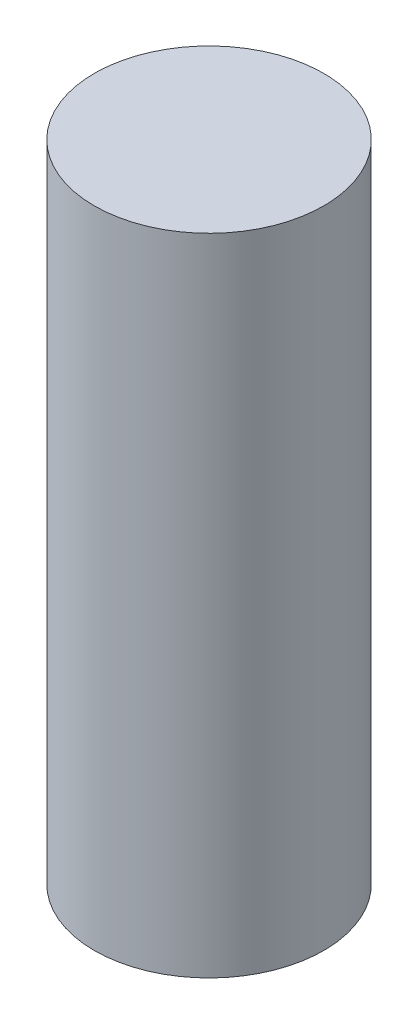
SolidWorks part; units mm, degrees
ref_plane "Front Plane" through (0, 0, 0) normal (0, 0, 1) x (1, 0, 0)
ref_plane "Top Plane" through (0, 0, 0) normal (0, 1, 0) x (1, 0, 0)
ref_plane "Right Plane" through (0, 0, 0) normal (1, 0, 0) x (0, 0, -1)
sketch "Sketch1" plane through (0, 0, 0) normal (0, 1, 0) x (1, 0, 0)
  circle A0 centre (0, 0) radius 17.399
  dimension "D1" = 34.798
extrude "Boss-Extrude1" add sketch "Sketch1" along normal blind 97.79
